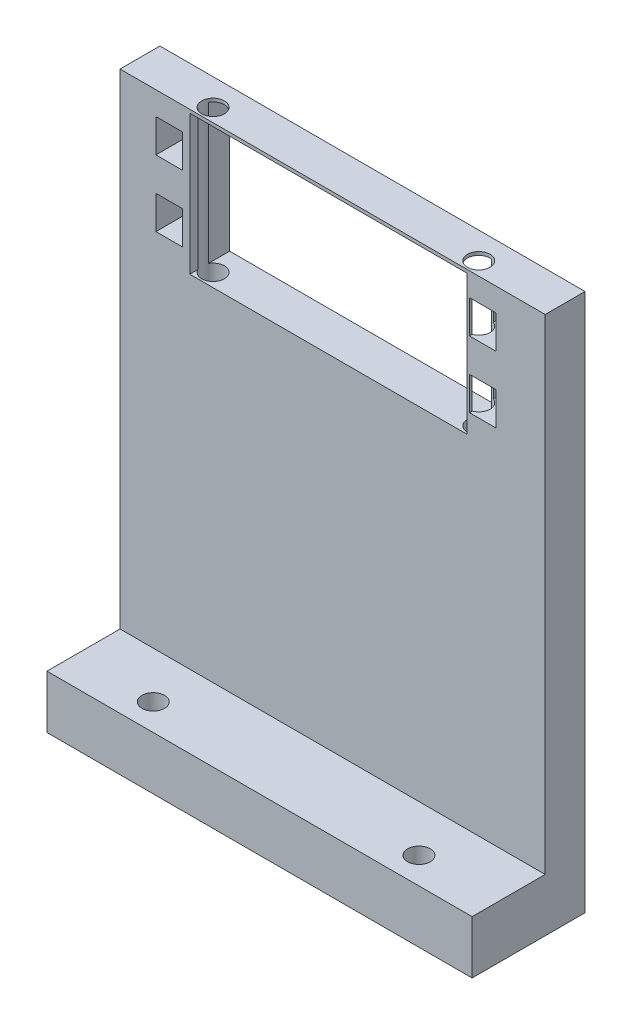
SolidWorks part; units mm, degrees
ref_plane "前视基准面" through (0, 0, 0) normal (0, 0, 1) x (1, 0, 0)
ref_plane "上视基准面" through (0, 0, 0) normal (0, 1, 0) x (1, 0, 0)
ref_plane "右视基准面" through (0, 0, 0) normal (1, 0, 0) x (0, 0, -1)
other "Configuration Table"
sketch "草图1" plane through (0, 0, 0) normal (0, 0, 1) x (1, 0, 0)
  line L1 (-21, 0) -> (43, 0)
  line L2 (-21, 0) -> (-21, 8)
  line L3 (-21, 8) -> (43, 8)
  line L4 (43, 0) -> (43, 8)
extrude "Servo_foot" add sketch "草图1" along normal blind 17
sketch "草图2" plane through (0, 0, 0) normal (0, 0, 1) x (1, 0, 0)
  line L1 (-21, 0) -> (43, 0)
  line L2 (-21, 0) -> (-21, 81)
  line L3 (-21, 81) -> (43, 81)
  line L4 (43, 0) -> (43, 81)
extrude "Servo_face_plate" add sketch "草图2" along normal blind 6
sketch "草图3" plane through (0, 0, 0) normal (0, 0, 1) x (1, 0, 0)
  line L1 (-10.5, 59.5) -> (31.2, 59.5)
  line L2 (-10.5, 59.5) -> (-10.5, 80.5)
  line L3 (-10.5, 80.5) -> (31.2, 80.5)
  line L4 (31.2, 59.5) -> (31.2, 80.5)
extrude "MG995_body_window_REFERENCE" cut sketch "草图3" against normal through all and the other way through all
sketch "草图4" plane through (0, 0, 0) normal (0, 0, 1) x (1, 0, 0)
  line L1 (-15.6, 62.5) -> (-11.6, 62.5)
  line L2 (-15.6, 62.5) -> (-15.6, 67.5)
  line L3 (-15.6, 67.5) -> (-11.6, 67.5)
  line L4 (-11.6, 62.5) -> (-11.6, 67.5)
  line L6 (-15.6, 72.5) -> (-11.6, 72.5)
  line L7 (-15.6, 72.5) -> (-15.6, 77.5)
  line L8 (-15.6, 77.5) -> (-11.6, 77.5)
  line L9 (-11.6, 72.5) -> (-11.6, 77.5)
  line L11 (31.6, 62.5) -> (35.6, 62.5)
  line L12 (31.6, 62.5) -> (31.6, 67.5)
  line L13 (31.6, 67.5) -> (35.6, 67.5)
  line L14 (35.6, 62.5) -> (35.6, 67.5)
  line L16 (31.6, 72.5) -> (35.6, 72.5)
  line L17 (31.6, 72.5) -> (31.6, 77.5)
  line L18 (31.6, 77.5) -> (35.6, 77.5)
  line L19 (35.6, 72.5) -> (35.6, 77.5)
extrude "MG995_47p2x10_reference_slots_VERIFY" cut sketch "草图4" against normal through all and the other way through all
sketch "草图5" plane through (0, 0, 0) normal (0, 1, 0) x (1, 0, 0)
  circle A0 centre (-9, -4) radius 1.7
  circle A1 centre (-9, -13) radius 1.7
  circle A2 centre (31, -4) radius 1.7
  circle A3 centre (31, -13) radius 1.7
extrude "Servo_foot_M3" cut sketch "草图5" against normal through all and the other way through all
